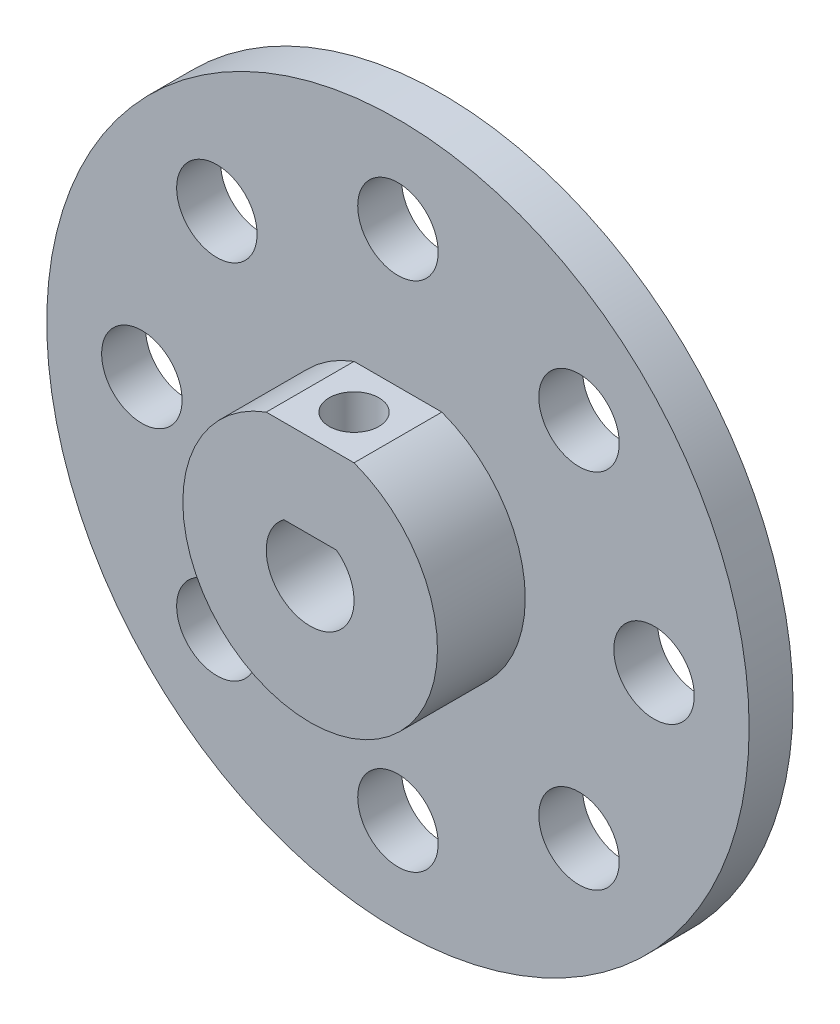
SolidWorks part; units mm, degrees
material "AISI 304"
ref_plane "Alzado" through (0, 0, 0) normal (0, 0, 1) x (1, 0, 0)
ref_plane "Planta" through (0, 0, 0) normal (0, 1, 0) x (1, 0, 0)
ref_plane "Vista lateral" through (0, 0, 0) normal (1, 0, 0) x (0, 0, -1)
sketch "Croquis1" plane through (0, 0, 0) normal (1, 0, 0) x (0, 0, -1)
  line L0 (0, 16.8101) -> (0, -16.8101) construction
  line L1 (-25.6232, 0) -> (25.6232, 0) construction
  line L2 (-5.25, 0) -> (5.25, 0)
  line L3 (5.25, 0) -> (5.25, 9)
  line L4 (5.25, 9) -> (3.75, 9)
  line L5 (3.75, 9) -> (3.75, 24)
  line L6 (3.75, 24) -> (0.75, 24)
  line L7 (0.75, 24) -> (0.75, 8.7)
  line L8 (0.75, 8.7) -> (-5.25, 8.7)
  line L9 (-5.25, 8.7) -> (-5.25, 0)
  point P5 (0, 0)
  point P8 (0, 0)
  dimension "D1" = 9
  dimension "D2" = 24
  dimension "D3" = 1.5
  dimension "D4" = 6
  dimension "D5" = 3
  dimension "D6" = 8.7
revolve "Revolución1" add sketch "Croquis1" angle 360 about L1
sketch "Croquis2" plane through (0, 0, 5.25) normal (0, 0, 1) x (1, 0, 0)
  line L0 (-1.8, 2.4) -> (1.8, 2.4)
  arc A0 (-1.8, 2.4) -> (1.8, 2.4) centre (0, 0) ccw
  dimension "D1" = 6
  dimension "D2" = 5.4
extrude "Cortar-Extruir1" cut sketch "Croquis2" against normal blind 10
sketch "Croquis3" plane through (0, 0, -3.75) normal (0, 0, -1) x (-1, 0, 0)
  circle A0 centre (0, 0) radius 17.5 construction
  point P3 (0, 17.5)
  point P7 (12.3744, 12.3744)
  point P8 (17.5, 0)
  point P9 (12.3744, -12.3744)
  point P10 (0, -17.5)
  point P11 (-12.3744, -12.3744)
  point P12 (-17.5, 0)
  point P13 (-12.3744, 12.3744)
  point P14 (0, 0)
  dimension "D1" = 35
  dimension "D2" = 8
hole_wizard "Taladro de margen para M51" positions "Croquis3D4" profile "Croquis9" hole size "M5" standard "Ansi Metric" end condition up to next
sketch3d "Croquis3D4"
  point P0 (0, 17.5, -3.75)
  point P3 (-12.3744, 12.3744, -3.75)
  point P6 (-17.5, 0, -3.75)
  point P9 (-12.3744, -12.3744, -3.75)
  point P12 (0, -17.5, -3.75)
  point P15 (12.3744, -12.3744, -3.75)
  point P18 (17.5, 0, -3.75)
  point P21 (12.3744, 12.3744, -3.75)
sketch "Croquis9" plane through (0, 17.5, -3.75) normal (1, 0, 0) x (0, 1, 0)
  line L0 (0, 0) -> (0, 3)
  line L1 (0, 3) -> (2.75, 3)
  line L2 (2.75, 3) -> (2.75, 0)
  line L5 (2.75, 0) -> (0, 0)
  line L11 (0, -6.35) -> (0, 107.95) construction
  dimension "Diámetro de taladro hasta el siguiente" = 5.5
  dimension "Profundidad de taladro hasta el siguiente" = 3
sketch "Croquis10" plane through (0, 0, 5.25) normal (0, 0, 1) x (1, 0, 0)
  line L0 (-3, 8.1664) -> (3, 8.1664)
  circle A0 centre (0, 0) radius 8.7 construction
  arc A1 (3, 8.1664) -> (-3, 8.1664) centre (0, 0) ccw
  dimension "D1" = 6
extrude "Cortar-Extruir2" cut sketch "Croquis10" against normal up to surface (6 mm away) up to face at (-2.75, 17.5, -0.75)
sketch "Croquis11" plane through (0, 8.1664, 0) normal (0, 1, 0) x (1, 0, 0)
  line L4 (-3, 0.75) -> (-3, -5.25)
  line L5 (-3, -5.25) -> (3, -5.25)
  line L6 (3, -5.25) -> (3, 0.75)
  line L7 (3, 0.75) -> (-3, 0.75)
  line L8 (-3, 0.75) -> (-3, -5.25)
  line L9 (-3, -5.25) -> (3, -5.25)
  line L10 (3, -5.25) -> (3, 0.75)
  line L11 (3, 0.75) -> (-3, 0.75)
  point P2 (0, -2.25)
  point P6 (-3, -2.25)
  point P8 (0, -5.25)
  dimension "D1" = 0
hole_wizard "Taladro de margen para M31" positions "Croquis3D5" profile "Croquis12" hole size "M3" standard "Ansi Metric"
sketch3d "Croquis3D5"
  point P0 (0, 8.1664, 2.25)
sketch "Croquis12" plane through (0, 8.1664, 2.25) normal (1, 0, 0) x (0, 0, 1)
  line L0 (0, 0) -> (0, 5.7664)
  line L1 (0, 5.7664) -> (1.7, 5.7664)
  line L2 (1.7, 5.7664) -> (1.7, 0)
  line L5 (1.7, 0) -> (0, 0)
  line L11 (0, -6.35) -> (0, 107.95) construction
  dimension "Diámetro de taladro hasta el siguiente" = 3.4
  dimension "Profundidad de taladro hasta el siguiente" = 5.7664
